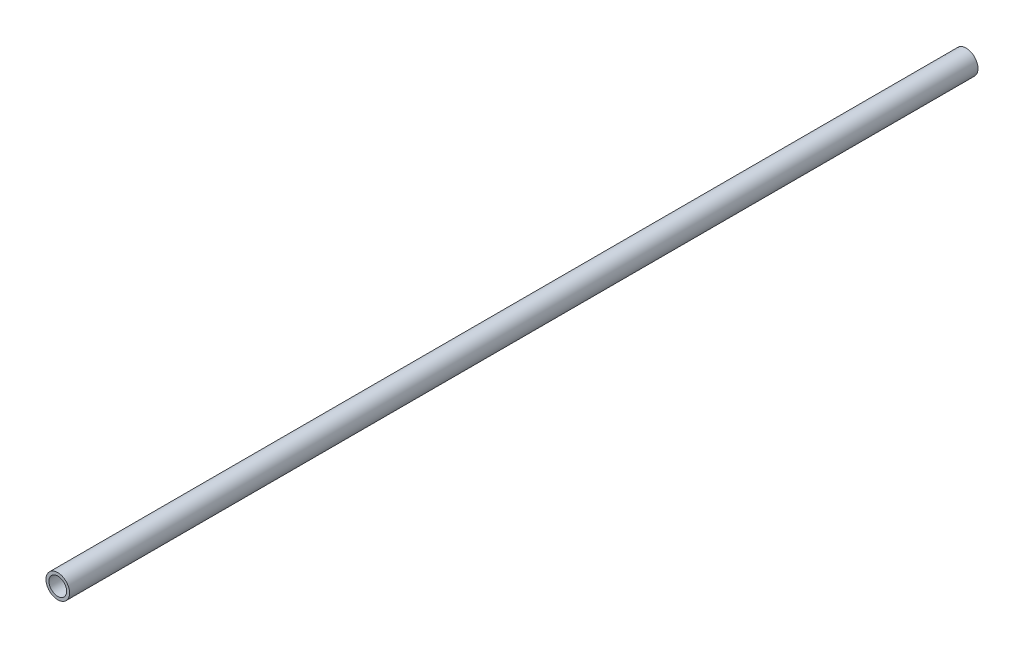
SolidWorks part; units mm, degrees
material "6061-T6 (SS)"
ref_plane "Front Plane" through (0, 0, 0) normal (0, 0, 1) x (1, 0, 0)
ref_plane "Top Plane" through (0, 0, 0) normal (0, 1, 0) x (1, 0, 0)
ref_plane "Right Plane" through (0, 0, 0) normal (1, 0, 0) x (0, 0, -1)
sketch "Sketch1" plane through (0, 0, 0) normal (0, 0, 1) x (1, 0, 0)
  circle A0 centre (0, 0) radius 4
  circle A1 centre (0, 0) radius 3
extrude "Compression_Tube" add sketch "Sketch1" along normal blind 308
